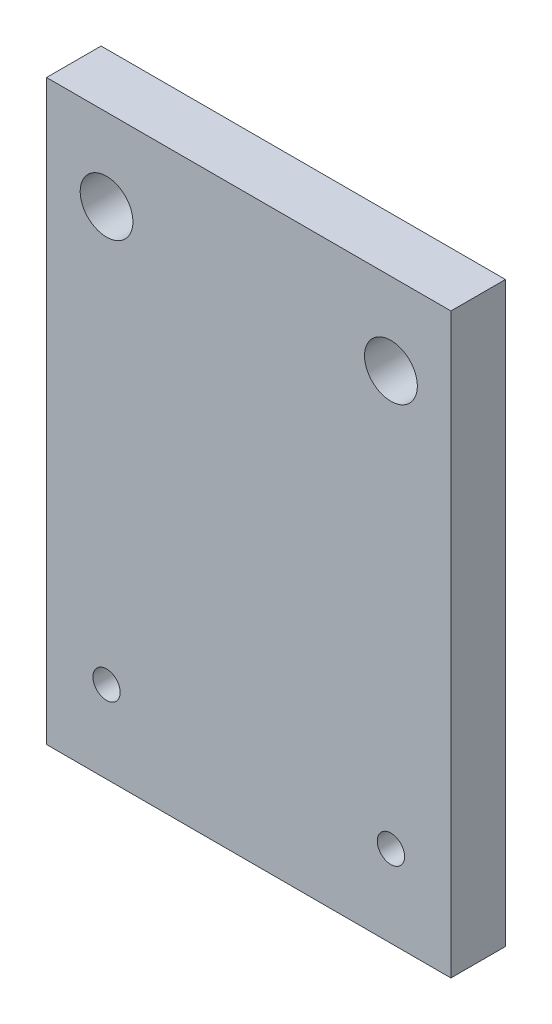
SolidWorks part; units mm, degrees
ref_plane "Front Plane" through (0, 0, 0) normal (0, 0, 1) x (1, 0, 0)
ref_plane "Top Plane" through (0, 0, 0) normal (0, 1, 0) x (1, 0, 0)
ref_plane "Right Plane" through (0, 0, 0) normal (1, 0, 0) x (0, 0, -1)
sketch "Sketch1" plane through (0, 0, 0) normal (0, 0, 1) x (1, 0, 0)
  line L1 (0, 0) -> (44.45, 0)
  line L2 (0, 0) -> (0, -63.5)
  line L3 (0, -63.5) -> (44.45, -63.5)
  line L4 (44.45, 0) -> (44.45, -63.5)
  circle A0 centre (6.595, -9) radius 2.9
  circle A1 centre (37.855, -9) radius 2.9
  circle A2 centre (6.595, -54.5) radius 1.5
  circle A3 centre (37.855, -54.5) radius 1.5
  dimension "D3" = 5.8
  dimension "D4" = 5.8
  dimension "D9" = 3
  dimension "D10" = 3
  dimension "D1" = 44.45
  dimension "D2" = 63.5
  dimension "D5" = 9
  dimension "D6" = 9
  dimension "D7" = 6.595
  dimension "D8" = 6.595
  dimension "D11" = 9
  dimension "D12" = 9
extrude "Boss-Extrude1" add sketch "Sketch1" along normal blind 5.9944
